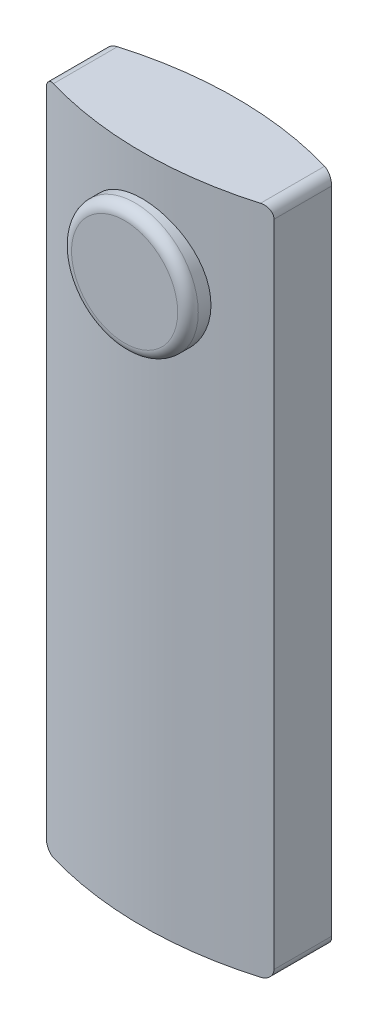
SolidWorks part; units mm, degrees
ref_plane "Front Plane" through (0, 0, 0) normal (0, 0, 1) x (1, 0, 0)
ref_plane "Top Plane" through (0, 0, 0) normal (0, 1, 0) x (1, 0, 0)
ref_plane "Right Plane" through (0, 0, 0) normal (1, 0, 0) x (0, 0, -1)
sketch "Sketch5" plane through (0, 0, 0) normal (0, 1, 0) x (1, 0, 0)
  line L0 (-22.1, 5.6) -> (-22.1, -5.6)
  line L1 (-22.1, -5.6) -> (22.1, -5.6) construction
  line L2 (-22.1, -5.6) -> (-22.1, 5.6) construction
  line L3 (-22.1, 5.6) -> (22.1, 5.6) construction
  line L4 (22.1, -5.6) -> (22.1, 5.6) construction
  line L5 (-22.1, -5.6) -> (22.1, 5.6) construction
  line L6 (-22.1, 5.6) -> (22.1, -5.6) construction
  line L7 (22.1, 5.6) -> (22.1, -5.6)
  line L8 (-56.4322, 0) -> (52.5725, 0) construction
  line L9 (0, 9.1) -> (0, -9.1) construction
  arc A1 (-22.1, 5.6) -> (22.1, 5.6) centre (0, -62.4229) cw
  arc A2 (-22.1, -5.6) -> (22.1, -5.6) centre (0, 62.4229) ccw
  point P0 (0, 0)
  dimension "D1" = 11.2
  dimension "D2" = 18.2
  dimension "D3" = 44.2
extrude "Boss-Extrude1" add sketch "Sketch5" along normal blind 130.12
sketch "Sketch6" plane through (0, 0, 0) normal (0, 0, 1) x (1, 0, 0)
  line L0 (-22.1, 0) -> (22.1, 0) construction
  circle A0 centre (0, 110) radius 12.3
  dimension "D2" = 24.6
  dimension "D1" = 110
extrude "Boss-Extrude2" add sketch "Sketch6" along normal mid plane 25
sketch "Sketch7" plane through (-22.1, 0, 0) normal (-1, 0, 0) x (0, 0, 1)
  line L0 (-5.6, 0) -> (5.6, 0) construction
  circle A0 centre (0, 94.5) radius 2.35
  circle A1 centre (0, 79.5) radius 2.35
  circle A2 centre (0, 64.5) radius 2.35
  dimension "D2" = 4.7
  dimension "D1" = 64.5
  dimension "D3" = 15
  dimension "D4" = 15
extrude "Boss-Extrude3" add sketch "Sketch7" along normal blind 2
fillet "Fillet1" radius 2 1 edges at (12.3, 110, 12.5)
fillet "Fillet2" radius 2 2 edges at (22.1, 130.12, 0) (-22.1, 130.12, 0)
fillet "Fillet3" radius 2 2 edges at (22.1, 0, 0) (-22.1, 0, 0)
